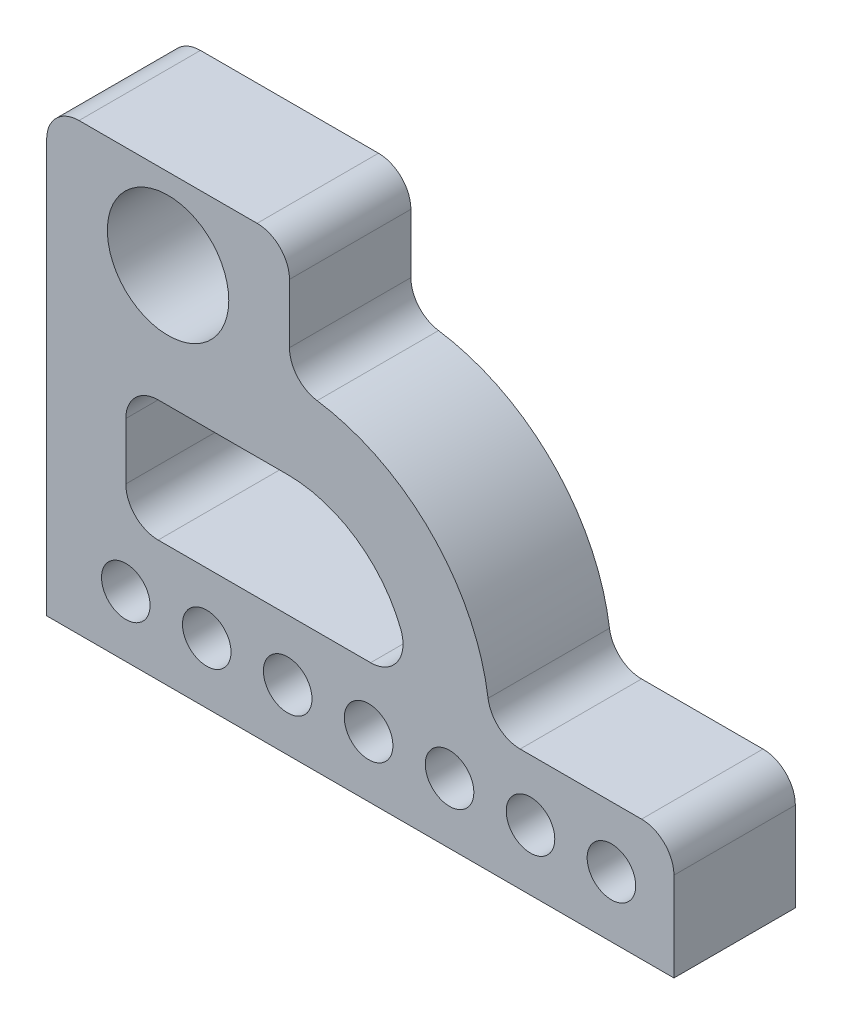
SolidWorks part; units mm, degrees
ref_plane "Front Plane" through (0, 0, 0) normal (0, 0, 1) x (1, 0, 0)
ref_plane "Top Plane" through (0, 0, 0) normal (0, 1, 0) x (1, 0, 0)
ref_plane "Right Plane" through (0, 0, 0) normal (1, 0, 0) x (0, 0, -1)
sketch "Sketch1" plane through (0, 0, 0) normal (0, 0, 1) x (1, 0, 0)
  line L0 (-59.5559, -15.5565) -> (95.4441, -15.5565)
  line L1 (-59.5559, -15.5565) -> (-59.5559, 86.4435)
  line L2 (-51.5559, 94.4435) -> (-7.5559, 94.4435)
  line L3 (0.4441, 86.4435) -> (0.4441, 71.8255)
  line L4 (95.4441, -15.5565) -> (95.4441, 6.4435)
  line L6 (87.4441, 14.4435) -> (57.4456, 14.4435)
  line L7 (0, 44.4435) -> (-32, 44.4435)
  line L8 (-40, 36.4435) -> (-40, 22.4435)
  line L9 (-32, 14.4435) -> (20.4939, 14.4435)
  arc A0 (49.5221, 21.34) -> (7.2794, 63.9107) centre (0, 14.4435) ccw
  circle A1 centre (-29.5559, 74.4435) radius 15
  arc A2 (27.9462, 25.3526) -> (0, 44.4435) centre (0, 14.4435) ccw
  circle A3 centre (-40, -0.5565) radius 6
  circle A4 centre (-20, -0.5565) radius 6
  circle A10 centre (0, -0.5565) radius 6
  circle A11 centre (20, -0.5565) radius 6
  circle A12 centre (40, -0.5565) radius 6
  circle A13 centre (60, -0.5565) radius 6
  circle A14 centre (80, -0.5565) radius 6
  arc A15 (-59.5559, 86.4435) -> (-51.5559, 94.4435) centre (-51.5559, 86.4435) cw
  arc A16 (0.4441, 86.4435) -> (-7.5559, 94.4435) centre (-7.5559, 86.4435) ccw
  arc A17 (7.2794, 63.9107) -> (0.4441, 71.8255) centre (8.4441, 71.8255) cw
  arc A18 (57.4456, 14.4435) -> (49.5221, 21.34) centre (57.4456, 22.4435) cw
  arc A19 (95.4441, 6.4435) -> (87.4441, 14.4435) centre (87.4441, 6.4435) ccw
  arc A20 (-40, 36.4435) -> (-32, 44.4435) centre (-32, 36.4435) cw
  arc A21 (-32, 14.4435) -> (-40, 22.4435) centre (-32, 22.4435) cw
  arc A22 (20.4939, 14.4435) -> (27.9462, 25.3526) centre (20.4939, 22.4435) ccw
  point P19 (-24.8247, -0.5565)
  point P20 (0, 0)
  point P23 (-7.6057, 0)
  point P24 (0, 0)
  point P25 (-5.3401, 0)
  point P26 (84.3799, 0)
  point P29 (66.2547, 0)
  point P30 (22.6878, -0.5565)
  point P32 (46.3169, 0)
  point P34 (37.9204, -0.5565)
  point P35 (23.2072, 0)
  point P36 (0, 0)
  point P37 (0, 0)
  point P38 (-136.7481, 23.3774)
  point P39 (0, 0)
  point P42 (58.047, -0.5565)
  point P45 (80.9195, -0.5565)
  point P48 (-59.5559, 94.4435)
  point P51 (0.4441, 94.4435)
  point P55 (50, 14.4435)
  point P58 (95.4441, 14.4435)
  point P61 (-40, 44.4435)
  point P64 (-40, 14.4435)
  point P67 (30, 14.4435)
  dimension "D1" = 60
  dimension "D2" = 50
  dimension "D7" = 30
  dimension "D9" = 30
  dimension "D10" = 40
  dimension "D12" = 20
  dimension "D13" = 30
  dimension "D14" = 15
  dimension "D15" = 12
  dimension "D20" = 20
  dimension "D21" = 20
  dimension "D22" = 8
  dimension "D23" = 8
  dimension "D6" = 8
  dimension "D24" = 8
  dimension "D25" = 8
  dimension "D26" = 8
  dimension "D27" = 8
  dimension "D28" = 8
  dimension "D3" = 30
  dimension "D4" = 110
  dimension "D5" = 155
  dimension "D8" = 20
  dimension "D11" = 30
  dimension "D16" = 20
  dimension "D17" = 20
  dimension "D18" = 20
  dimension "D19" = 20
extrude "Boss-Extrude1" add sketch "Sketch1" along normal blind 30
